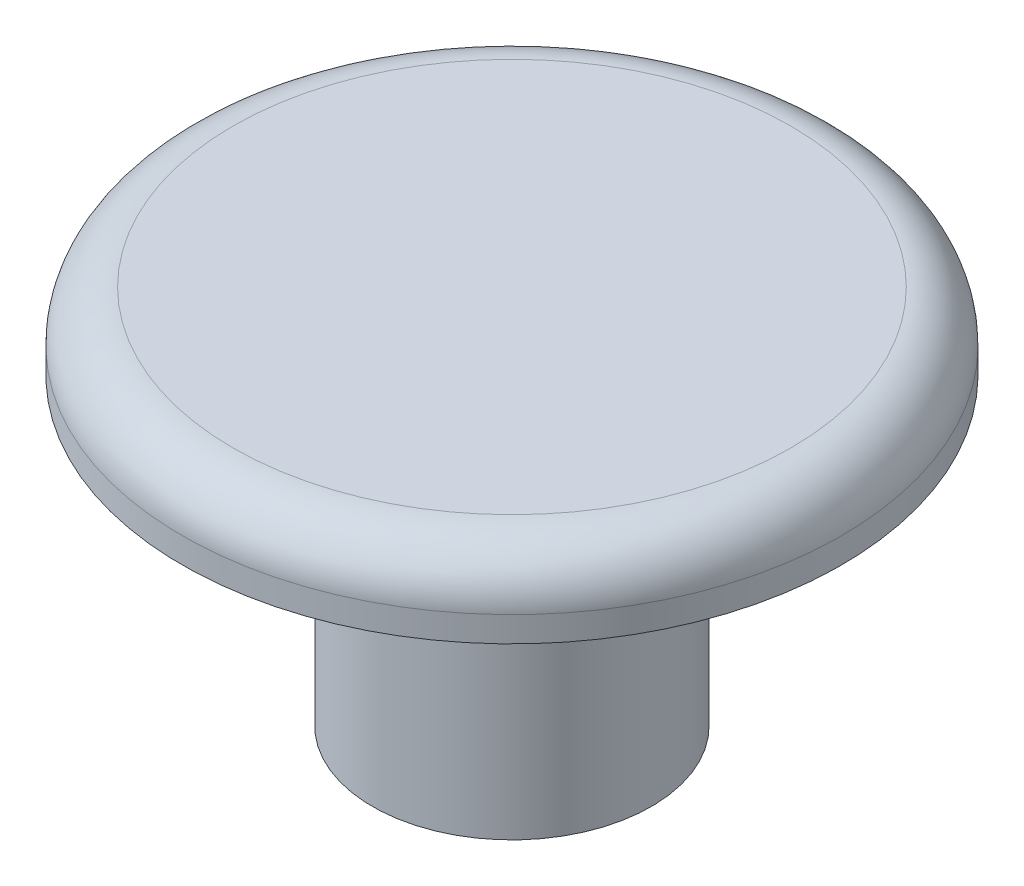
SolidWorks part; units mm, degrees
ref_plane "Front Plane" through (0, 0, 0) normal (0, 0, 1) x (1, 0, 0)
ref_plane "Top Plane" through (0, 0, 0) normal (0, 1, 0) x (1, 0, 0)
ref_plane "Right Plane" through (0, 0, 0) normal (1, 0, 0) x (0, 0, -1)
sketch "Sketch1" plane through (0, 0, 0) normal (0, 0, 1) x (1, 0, 0)
  line L0 (0, 0) -> (0, 15) construction
  line L1 (0, 15) -> (11, 15)
  line L2 (13, 13) -> (13, 12)
  line L3 (13, 12) -> (5.5, 12)
  line L4 (5.5, 12) -> (5.5, 0)
  line L5 (5.5, 0) -> (0, 0)
  line L6 (0, 0) -> (0, 15)
  arc A0 (11, 15) -> (13, 13) centre (11, 13) cw
  dimension "D3" = 2
  dimension "D1" = 15
  dimension "D2" = 11
  dimension "D4" = 3
  dimension "D5" = 5.5
revolve "Revolve1" add sketch "Sketch1" angle 360 about L0
